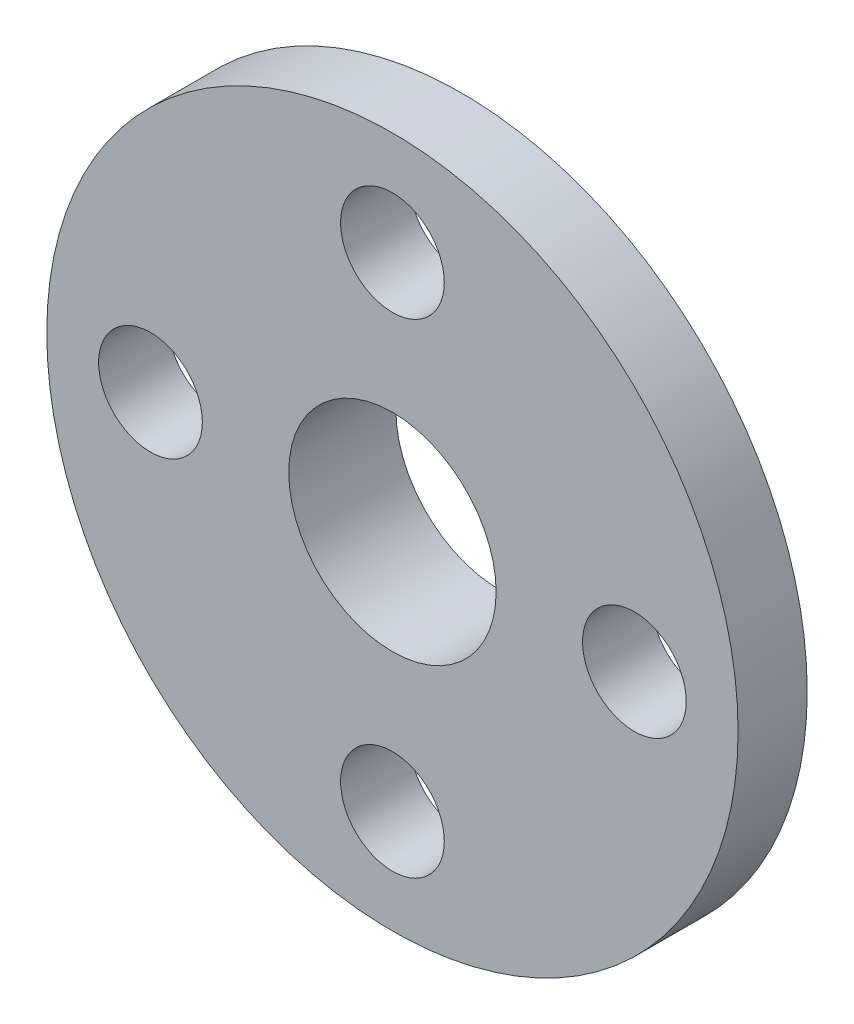
SolidWorks part; units mm, degrees
ref_plane "正面" through (0, 0, 0) normal (0, 0, 1) x (1, 0, 0)
ref_plane "平面" through (0, 0, 0) normal (0, 1, 0) x (1, 0, 0)
ref_plane "右側面" through (0, 0, 0) normal (1, 0, 0) x (0, 0, -1)
sketch "ｽｹｯﾁ1" plane through (0, 0, 0) normal (0, 0, 1) x (1, 0, 0)
  circle A0 centre (0, 0) radius 10
  circle A1 centre (0, 0) radius 3
  circle A2 centre (-7, 0) radius 1.5
  circle A3 centre (7, 0) radius 1.5
  circle A4 centre (0, 7) radius 1.5
  circle A5 centre (0, -7) radius 1.5
  dimension "D1" = 20
  dimension "D2" = 6
  dimension "D4" = 7
  dimension "D5" = 3
  dimension "D6" = 3
  dimension "D7" = 3
  dimension "D8" = 3
  dimension "D9" = 7
  dimension "D10" = 7
  dimension "D11" = 90
  dimension "D12" = 90
  dimension "D13" = 90
  dimension "D3" = 7
extrude "ﾎﾞｽ - 押し出し1" add sketch "ｽｹｯﾁ1" along normal blind 2
sketch "ｽｹｯﾁ2" plane through (0, 0, 0) normal (0, 0, -1) x (-1, 0, 0)
  circle A0 centre (0, 0) radius 3
  circle A1 centre (0, 0) radius 4.5
  dimension "D1" = 1.5
extrude "ﾎﾞｽ - 押し出し2" add sketch "ｽｹｯﾁ2" along normal blind 1.1
